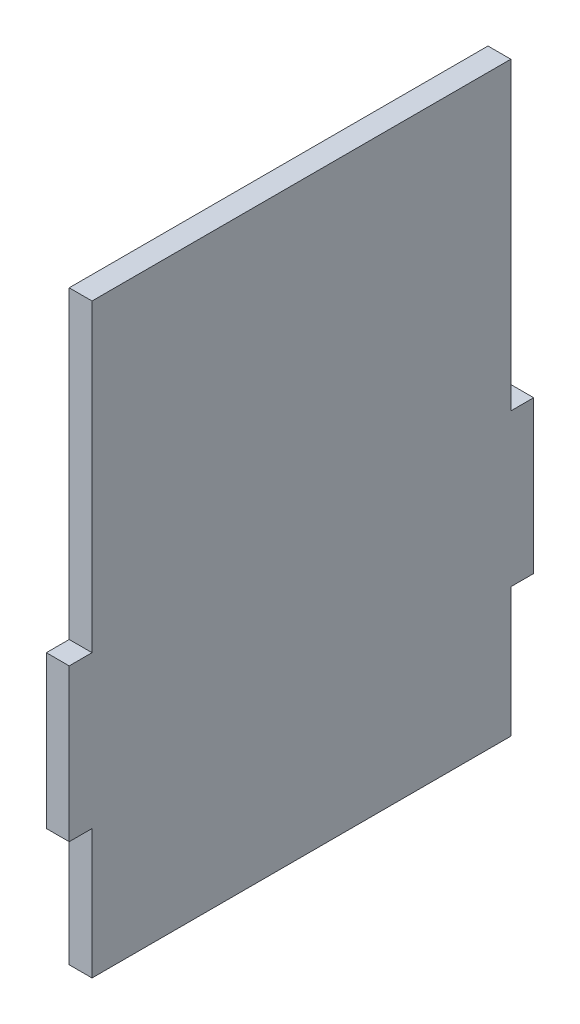
SolidWorks part; units mm, degrees
material "Acrilico TEC"
ref_plane "Front Plane" through (0, 0, 0) normal (0, 0, 1) x (1, 0, 0)
ref_plane "Top Plane" through (0, 0, 0) normal (0, 1, 0) x (1, 0, 0)
ref_plane "Right Plane" through (0, 0, 0) normal (1, 0, 0) x (0, 0, -1)
sketch "Sketch1" plane through (0, 0, 0) normal (1, 0, 0) x (0, 0, -1)
  line L0 (-27.5, 0) -> (27.5, 0)
  line L1 (27.5, 0) -> (27.5, 17)
  line L2 (27.5, 17) -> (30.5, 17)
  line L3 (30.5, 17) -> (30.5, 37)
  line L4 (30.5, 37) -> (27.5, 37)
  line L5 (27.5, 37) -> (27.5, 77)
  line L6 (27.5, 77) -> (-27.5, 77)
  line L7 (0, 77) -> (0, 0) construction
  line L8 (-27.5, 37) -> (-27.5, 77)
  line L9 (-30.5, 37) -> (-27.5, 37)
  line L10 (-30.5, 17) -> (-30.5, 37)
  line L11 (-27.5, 17) -> (-30.5, 17)
  line L12 (-27.5, 0) -> (-27.5, 17)
  dimension "D1" = 27.5
  dimension "D2" = 17
  dimension "D3" = 3
  dimension "D4" = 40
  dimension "D5" = 20
extrude "Boss-Extrude1" add sketch "Sketch1" along normal blind 3
